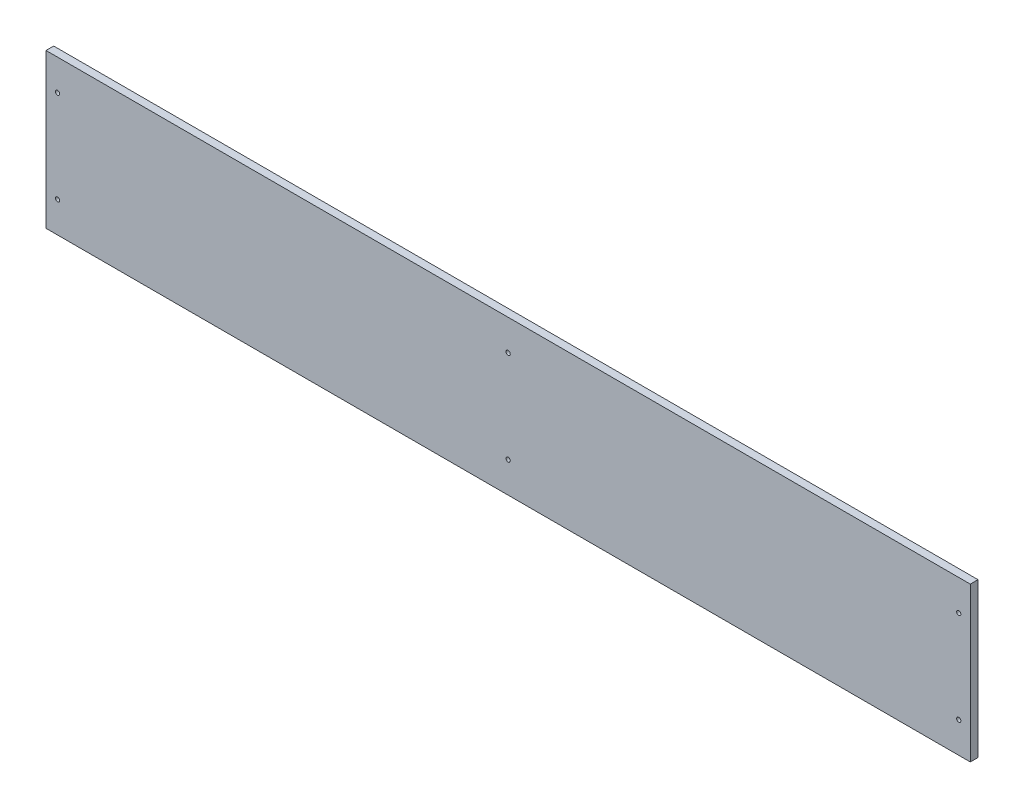
SolidWorks part; units mm, degrees
ref_plane "Plan de face" through (0, 0, 0) normal (0, 0, 1) x (1, 0, 0)
ref_plane "Plan de dessus" through (0, 0, 0) normal (0, 1, 0) x (1, 0, 0)
ref_plane "Plan de droite" through (0, 0, 0) normal (1, 0, 0) x (0, 0, -1)
sketch "Esquisse1" plane through (0, 0, 0) normal (0, 0, 1) x (1, 0, 0)
  line L1 (0, 0) -> (1200, 0)
  line L2 (0, 0) -> (0, -200)
  line L3 (0, -200) -> (1200, -200)
  line L4 (1200, 0) -> (1200, -200)
  dimension "D1" = 200
  dimension "D2" = 1200
extrude "Boss.-Extru.1" add sketch "Esquisse1" along normal blind 10
sketch "Esquisse2" plane through (0, 0, 10) normal (0, 0, 1) x (1, 0, 0)
  line L0 (0, 0) -> (0, -200) construction
  line L1 (1200, -200) -> (1200, 0) construction
  line L2 (1200, 0) -> (0, 0) construction
  line L3 (0, -200) -> (1200, -200) construction
  line L4 (0, -200) -> (1200, -200) construction
  line L5 (1200, 0) -> (0, 0) construction
  circle A0 centre (15, -40) radius 2.75
  circle A1 centre (15, -160) radius 2.75
  circle A2 centre (1185, -40) radius 2.75
  circle A3 centre (1185, -160) radius 2.75
  circle A4 centre (600, -40) radius 2.75
  circle A5 centre (600, -160) radius 2.75
  point P24 (600, 0)
  point P25 (600, -200)
  dimension "D5" = 5.5
  dimension "D6" = 5.5
  dimension "D7" = 5.5
  dimension "D8" = 5.5
  dimension "D13" = 5.5
  dimension "D14" = 5.5
  dimension "D1" = 15
  dimension "D2" = 15
  dimension "D3" = 15
  dimension "D4" = 15
  dimension "D9" = 40
  dimension "D10" = 40
  dimension "D11" = 40
  dimension "D12" = 40
  dimension "D15" = 40
  dimension "D16" = 40
  dimension "D17" = 0
  dimension "D18" = 0
extrude "Enlèv. mat.-Extru.1" cut sketch "Esquisse2" against normal blind 10
chamfer "Chanfrein1" distance 2.5 angle 45 6 edges at (17.75, -160, 0) (17.75, -40, 0) (1187.75, -40, 0) (1187.75, -160, 0) (602.75, -160, 0) (602.75, -40, 0)
